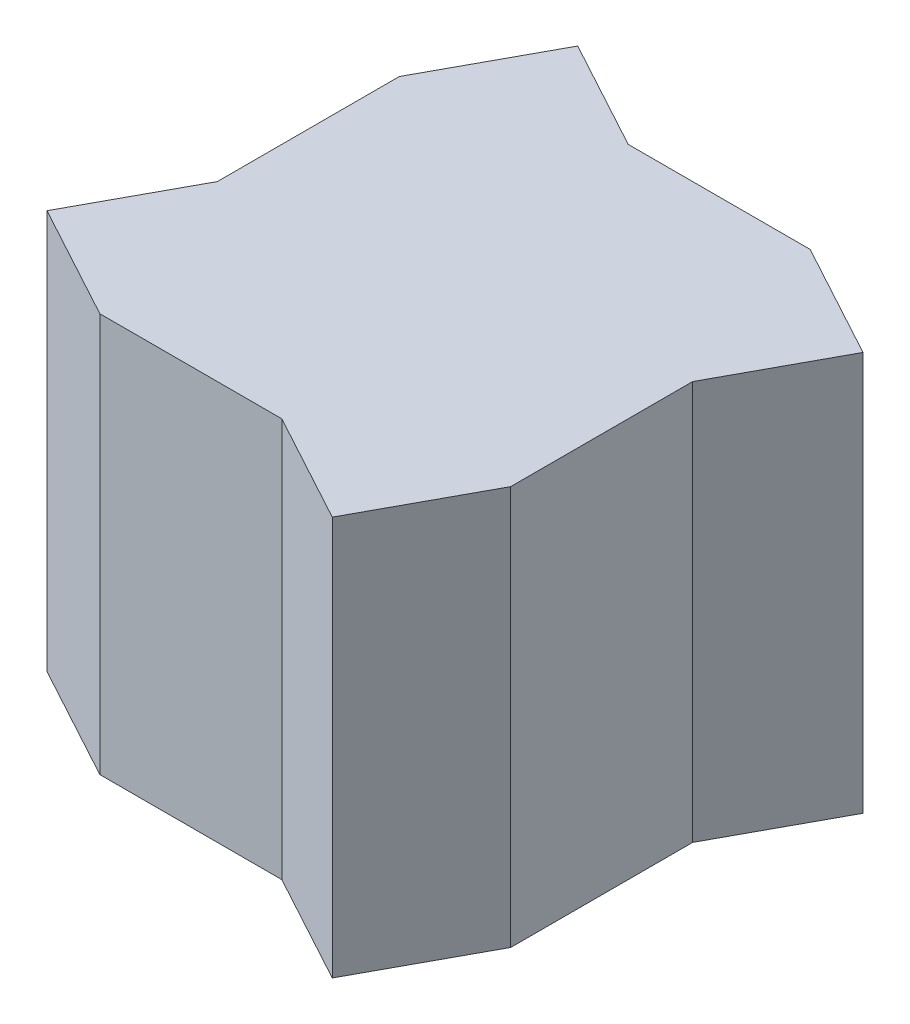
SolidWorks part; units mm, degrees
ref_plane "Front Plane" through (0, 0, 0) normal (0, 0, 1) x (1, 0, 0)
ref_plane "Top Plane" through (0, 0, 0) normal (0, 1, 0) x (1, 0, 0)
ref_plane "Right Plane" through (0, 0, 0) normal (1, 0, 0) x (0, 0, -1)
sketch "Sketch1" plane through (0, 0, 0) normal (0, 1, 0) x (1, 0, 0)
  line L0 (0, 0) -> (0, 6.8376) construction
  line L1 (11.75, -21.25) -> (-11.75, 21.25) construction
  line L2 (21.25, 11.75) -> (-21.25, -11.75) construction
  line L3 (-16.5, 12.5) -> (-11.75, 21.25) construction
  line L4 (-16.5, -3) -> (-21.25, -11.75) construction
  line L5 (-16.5, 12.5) -> (-16.5, -3) construction
  line L6 (-12.5, -16.5) -> (-21.25, -11.75) construction
  line L7 (3, -16.5) -> (11.75, -21.25) construction
  line L8 (-12.5, -16.5) -> (3, -16.5) construction
  line L9 (16.5, -12.5) -> (11.75, -21.25) construction
  line L10 (16.5, 3) -> (21.25, 11.75) construction
  line L11 (16.5, -12.5) -> (16.5, 3) construction
  line L12 (12.5, 16.5) -> (21.25, 11.75) construction
  line L13 (-3, 16.5) -> (-11.75, 21.25) construction
  line L14 (12.5, 16.5) -> (-3, 16.5) construction
  line L15 (-17.5, 12.7539) -> (-12.1518, 22.6059)
  line L16 (-2.7461, 17.5) -> (-12.1518, 22.6059)
  line L17 (12.7539, 17.5) -> (-2.7461, 17.5)
  line L18 (12.7539, 17.5) -> (22.6059, 12.1518)
  line L19 (17.5, 2.7461) -> (22.6059, 12.1518)
  line L20 (17.5, -12.7539) -> (17.5, 2.7461)
  line L21 (17.5, -12.7539) -> (12.1518, -22.6059)
  line L22 (2.7461, -17.5) -> (12.1518, -22.6059)
  line L23 (-12.7539, -17.5) -> (2.7461, -17.5)
  line L24 (-12.7539, -17.5) -> (-22.6059, -12.1518)
  line L25 (-17.5, -2.7461) -> (-22.6059, -12.1518)
  line L26 (-17.5, 12.7539) -> (-17.5, -2.7461)
  point P18 (-16.5, 4.75)
  point P19 (-4.75, -16.5)
  point P20 (16.5, -4.75)
  point P21 (4.75, 16.5)
  dimension "D1" = 9.9562
  dimension "D2" = 9.9562
  dimension "D3" = 15.5
  dimension "D4" = 33
  dimension "D6" = 35
  dimension "D5" = 1
extrude "Boss-Extrude1" add sketch "Sketch1" along normal blind 34
